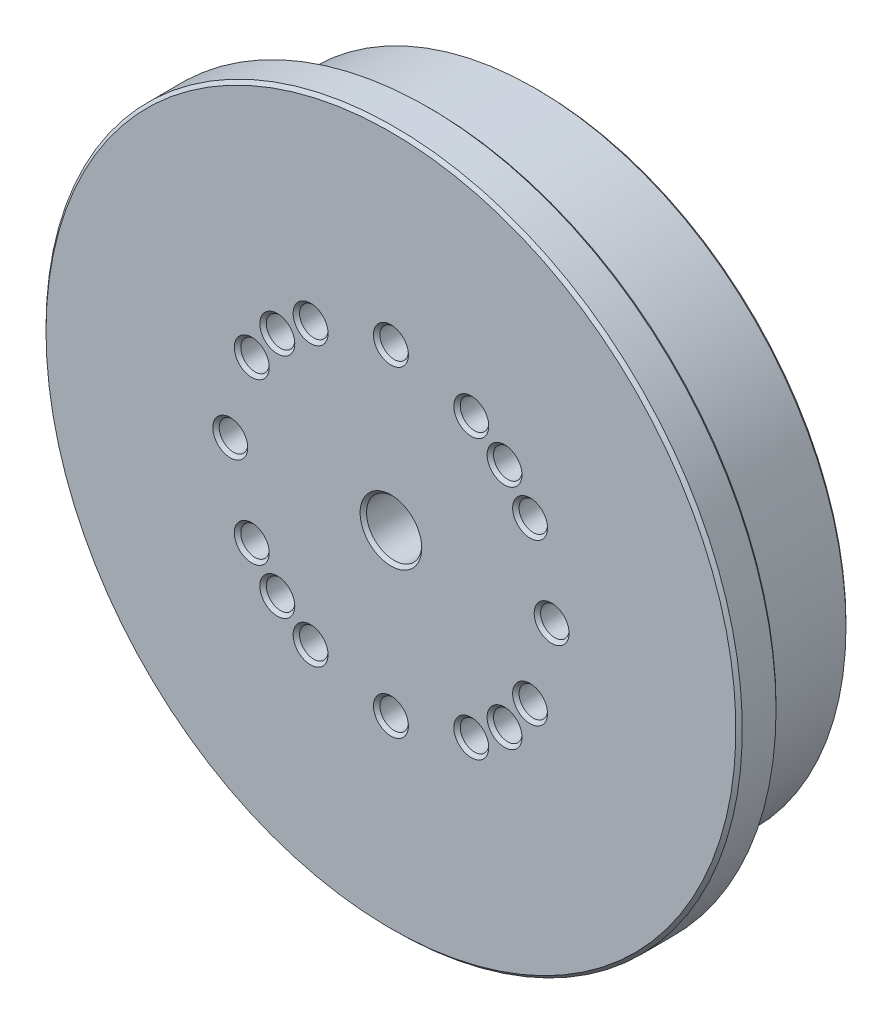
SolidWorks part; units mm, degrees
ref_plane "Front Plane" through (0, 0, 0) normal (0, 0, 1) x (1, 0, 0)
ref_plane "Top Plane" through (0, 0, 0) normal (0, 1, 0) x (1, 0, 0)
ref_plane "Right Plane" through (0, 0, 0) normal (1, 0, 0) x (0, 0, -1)
sketch "Sketch1" plane through (0, 0, 0) normal (0, 0, 1) x (1, 0, 0)
  circle A0 centre (0, 0) radius 73.7362
  dimension "D1" = 147.4724
extrude "Main" add sketch "Sketch1" along normal blind 25.4
sketch "Sketch2" plane through (0, 0, 25.4) normal (0, 0, 1) x (1, 0, 0)
  circle A0 centre (0, 0) radius 82.55
  dimension "D1" = 165.1
extrude "Shoulder" add sketch "Sketch2" along normal blind 9.525
sketch "Sketch3" plane through (0, 0, 34.925) normal (0, 0, 1) x (1, 0, 0)
  line L0 (0, 0) -> (0, 38.1) construction
  line L1 (0, 0) -> (38.1, 0) construction
  line L2 (0, 0) -> (0, -38.1) construction
  line L3 (0, 0) -> (-38.1, 0) construction
  line L4 (0, 0) -> (26.9408, 26.9408) construction
  line L5 (0, 0) -> (26.9408, -26.9408) construction
  line L6 (0, 0) -> (-26.9408, -26.9408) construction
  line L7 (-26.9408, 26.9408) -> (0, 0) construction
  line L8 (-32.9956, 19.05) -> (0, 0) construction
  line L9 (-19.05, 32.9956) -> (0, 0) construction
  line L10 (19.05, 32.9956) -> (0, 0) construction
  line L11 (32.9956, 19.05) -> (0, 0) construction
  line L12 (0, 0) -> (-32.9956, -19.05) construction
  line L13 (0, 0) -> (-19.05, -32.9956) construction
  line L14 (0, 0) -> (19.05, -32.9956) construction
  line L15 (0, 0) -> (32.9956, -19.05) construction
  circle A0 centre (0, 38.1) radius 3.175
  circle A1 centre (26.9408, 26.9408) radius 3.175
  circle A2 centre (38.1, 0) radius 3.175
  circle A3 centre (26.9408, -26.9408) radius 3.175
  circle A4 centre (0, -38.1) radius 3.175
  circle A5 centre (-38.1, 0) radius 3.175
  circle A6 centre (-26.9408, -26.9408) radius 3.175
  circle A7 centre (-26.9408, 26.9408) radius 3.175
  circle A8 centre (-19.05, 32.9956) radius 3.175
  circle A9 centre (19.05, 32.9956) radius 3.175
  circle A10 centre (32.9956, 19.05) radius 3.175
  circle A11 centre (-32.9956, 19.05) radius 3.175
  circle A12 centre (-32.9956, -19.05) radius 3.175
  circle A13 centre (-19.05, -32.9956) radius 3.175
  circle A14 centre (19.05, -32.9956) radius 3.175
  circle A15 centre (32.9956, -19.05) radius 3.175
  point P1 (0, 38.1)
  point P4 (38.1, 0)
  point P5 (0, -38.1)
  point P6 (-38.1, 0)
  point P8 (26.9408, -26.9408)
  point P9 (-26.9408, -26.9408)
  point P16 (-26.9408, 26.9408)
  point P18 (-19.05, 32.9956)
  point P20 (19.05, 32.9956)
  point P22 (32.9956, 19.05)
  point P24 (-32.9956, 19.05)
  point P27 (-32.9956, -19.05)
  point P28 (-19.05, -32.9956)
  point P29 (19.05, -32.9956)
  point P30 (32.9956, -19.05)
  point P47 (26.9408, 26.9408)
  dimension "D4" = 6.35
  dimension "D1" = 45
  dimension "D2" = 90
  dimension "D3" = 90
  dimension "D5" = 38.1
  dimension "D6" = 90
  dimension "D7" = 30
  dimension "D8" = 30
  dimension "D9" = 30
  dimension "D10" = 30
  dimension "D11" = 30
  dimension "D12" = 30
  dimension "D13" = 30
  dimension "D14" = 30
hole_wizard "1/4 Clearance Hole1" positions "Sketch3" profile "Sketch4" hole size "1/4" standard "ANSI Inch" end condition through all
sketch "Sketch4" plane through (26.9408, 26.9408, 34.925) normal (1, 0, 0) x (0, -1, 0)
  line L0 (0, 0) -> (0, 34.925)
  line L1 (0, 34.925) -> (3.3782, 34.925)
  line L2 (3.3782, 34.925) -> (3.3782, 0)
  line L5 (3.3782, 0) -> (0, 0)
  line L11 (0, -6.35) -> (0, 107.95) construction
  dimension "Thru Hole Dia." = 6.7564
  dimension "Thru Hole Depth" = 34.925
sketch "Sketch5" plane through (0, 0, 34.925) normal (0, 0, 1) x (1, 0, 0)
  point P0 (0, 0)
  point P3 (124.4536, 85.4446)
hole_wizard "1/2 Clearance Hole1" positions "Sketch5" profile "Sketch6" hole size "1/2" standard "ANSI Inch" end condition through all
sketch "Sketch6" plane through (0, 0, 34.925) normal (1, 0, 0) x (0, -1, 0)
  line L0 (0, 0) -> (0, 34.925)
  line L1 (0, 34.925) -> (6.5481, 34.925)
  line L2 (6.5481, 34.925) -> (6.5481, 0)
  line L5 (6.5481, 0) -> (0, 0)
  line L11 (0, -6.35) -> (0, 107.95) construction
  dimension "Thru Hole Dia." = 13.0962
  dimension "Thru Hole Depth" = 34.925
chamfer "Chamfer1" distance 0.762 angle 45 37 edges at (73.7362, 0, 0) (82.55, 0, 34.925) (82.55, 0, 25.4) (30.319, 26.9408, 0) (36.3738, -19.05, 0) (22.4282, -32.9956, 0) (-15.6718, -32.9956, 0) (-29.6174, -19.05, 0) (-29.6174, 19.05, 0) (36.3738, 19.05, 0) (22.4282, 32.9956, 0) (-15.6718, 32.9956, 0) (-23.5626, 26.9408, 0) (-23.5626, -26.9408, 0) (30.319, -26.9408, 0) (-34.7218, 0, 0) (3.3782, -38.1, 0) (41.4782, 0, 0) (3.3782, 38.1, 0) (6.5481, 0, 0) (30.319, 26.9408, 34.925) (36.3738, -19.05, 34.925) (22.4282, -32.9956, 34.925) (-15.6718, -32.9956, 34.925) (-29.6174, -19.05, 34.925) (-29.6174, 19.05, 34.925) (36.3738, 19.05, 34.925) (22.4282, 32.9956, 34.925) (-15.6718, 32.9956, 34.925) (-23.5626, 26.9408, 34.925) (-23.5626, -26.9408, 34.925) (30.319, -26.9408, 34.925) (-34.7218, 0, 34.925) (3.3782, -38.1, 34.925) (41.4782, 0, 34.925) (3.3782, 38.1, 34.925) (6.5481, 0, 34.925)
equation "\"ID\"= 5.806"
equation "\"D1@Sketch1\"=\"ID\""
